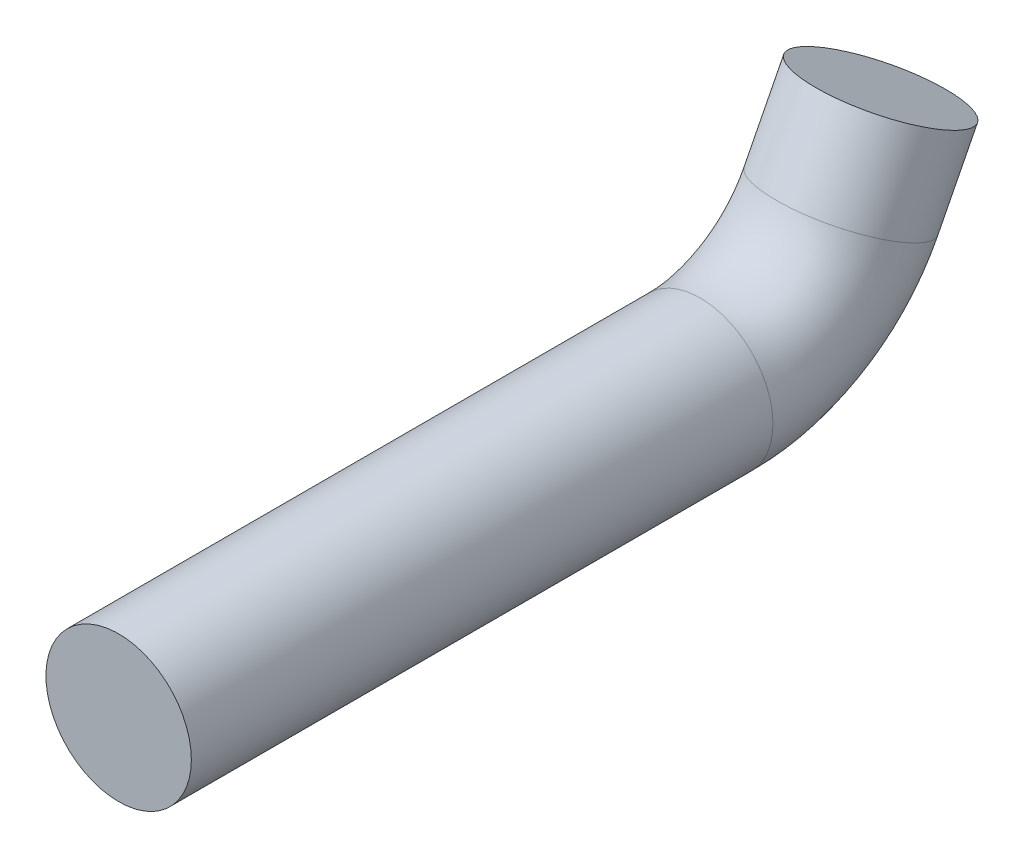
SolidWorks part; units mm, degrees
ref_plane "Front Plane" through (0, 0, 0) normal (0, 0, 1) x (1, 0, 0)
ref_plane "Top Plane" through (0, 0, 0) normal (0, 1, 0) x (1, 0, 0)
ref_plane "Right Plane" through (0, 0, 0) normal (1, 0, 0) x (0, 0, -1)
sketch "Sketch1" plane through (0, 0, 0) normal (0, 0, 1) x (1, 0, 0)
  circle A0 centre (0, 0) radius 1905
extrude "Boss-Extrude1" add sketch "Sketch1" along normal blind 15138.4
sketch "Sketch2" plane through (0, 0, 0) normal (0, 0, -1) x (-1, 0, 0)
  circle A0 centre (0, 0) radius 1905
sketch "Sketch3" plane through (0, 0, 0) normal (1, 0, 0) x (0, 0, -1)
  line L0 (0, 0) -> (101.6, 0)
  arc A0 (101.6, 0) -> (3790.5452, 2260.5885) centre (101.6, 4140.2) ccw
sweep "Sweep1" add profiles "Sketch2" path "Sketch3"
sketch "Sketch4" plane through (0, 3327.9723, -1695.6866) normal (0, 0.891, -0.454) x (1, 0, 0)
  circle A0 centre (0, 2351.1148) radius 1905
extrude "Boss-Extrude2" add sketch "Sketch4" along normal blind 2286
